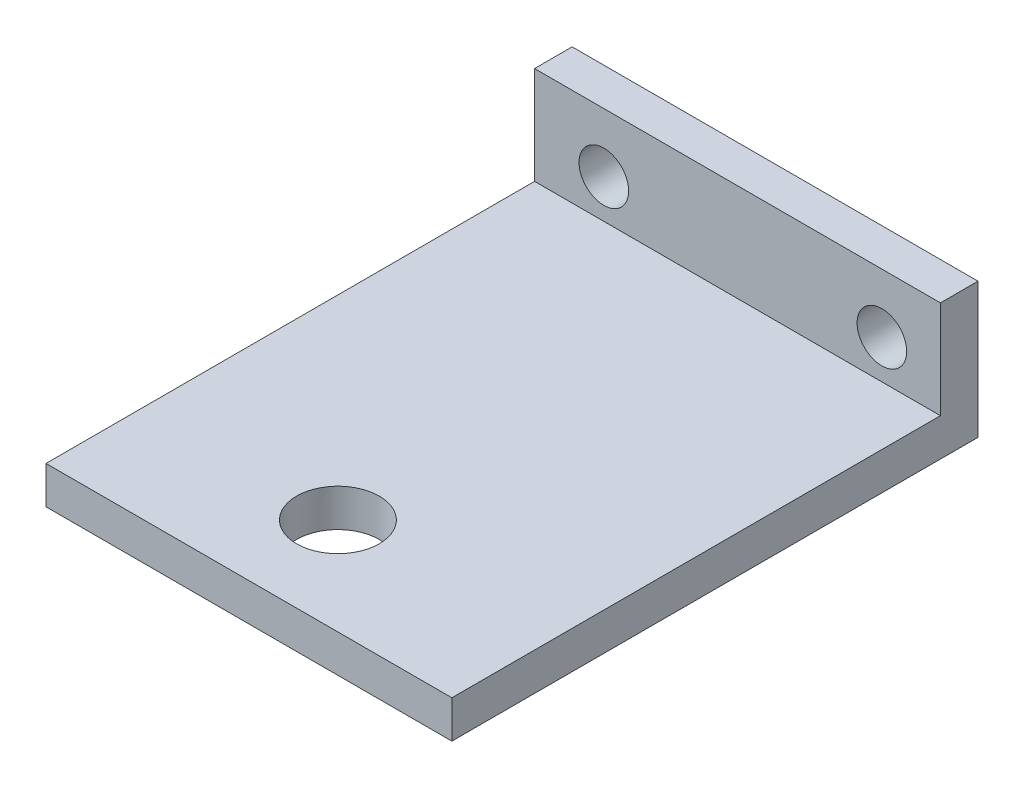
SolidWorks part; units mm, degrees
ref_plane "Plan de face" through (0, 0, 0) normal (0, 0, 1) x (1, 0, 0)
ref_plane "Plan de dessus" through (0, 0, 0) normal (0, 1, 0) x (1, 0, 0)
ref_plane "Plan de droite" through (0, 0, 0) normal (1, 0, 0) x (0, 0, -1)
sketch "Esquisse1" plane through (0, 0, 0) normal (0, 0, 1) x (1, 0, 0)
  line L1 (-27, -9) -> (27, -9)
  line L2 (-27, -9) -> (-27, 9)
  line L3 (-27, 9) -> (27, 9)
  line L4 (27, -9) -> (27, 9)
  line L5 (-27, -9) -> (27, 9) construction
  line L6 (-27, 9) -> (27, -9) construction
  point P0 (0, 0)
  dimension "D1" = 54
  dimension "D2" = 18
extrude "Boss.-Extru.1" add sketch "Esquisse1" along normal blind 70
sketch "Esquisse2" plane through (0, 9, 0) normal (0, 1, 0) x (1, 0, 0)
  line L8 (22, -5) -> (-22, -5)
  line L9 (-22, -5) -> (-22, -65)
  line L10 (-22, -65) -> (22, -65)
  line L11 (22, -65) -> (22, -5)
  line L12 (42.5059, -5) -> (-47.38, -5)
  line L13 (-47.38, -5) -> (-47.38, -79.5648)
  line L14 (-47.38, -79.5648) -> (42.5059, -79.5648)
  line L15 (42.5059, -79.5648) -> (42.5059, -5)
  dimension "D1" = 5
extrude "Enlèv. mat.-Extru.1" cut sketch "Esquisse2" against normal blind 13
hole_wizard "M6 Clearance Hole1" positions "Sketch2" profile "Sketch1" hole size "M6" standard "ANSI Metric" end condition through all
sketch "Sketch2" plane through (0, 0, 5) normal (0, 0, 1) x (1, 0, 0)
  point P0 (19.2116, 1.1447)
  point P2 (-17.7824, 1.1447)
sketch "Sketch1" plane through (19.2116, 1.1447, 5) normal (1, 0, 0) x (0, -1, 0)
  line L0 (0, 0) -> (0, 5)
  line L1 (0, 5) -> (3.3, 5)
  line L2 (3.3, 5) -> (3.3, 0)
  line L5 (3.3, 0) -> (0, 0)
  line L11 (0, -6.35) -> (0, 107.95) construction
  dimension "Thru Hole Dia." = 6.6
  dimension "Thru Hole Depth" = 5
hole_wizard "M10 Clearance Hole1" positions "Sketch5" profile "Sketch3" hole size "M10" standard "ANSI Metric" end condition through all
sketch "Sketch5" plane through (0, -9, 0) normal (0, -1, 0) x (-1, 0, 0)
  point P0 (1.0698, -57.0922)
sketch "Sketch3" plane through (-1.0698, -9, 57.0922) normal (1, 0, 0) x (0, 0, -1)
  line L0 (0, 0) -> (0, 18)
  line L1 (0, 18) -> (5.5, 18)
  line L2 (5.5, 18) -> (5.5, 0)
  line L5 (5.5, 0) -> (0, 0)
  line L11 (0, -6.35) -> (0, 107.95) construction
  dimension "Thru Hole Dia." = 11
  dimension "Thru Hole Depth" = 18
